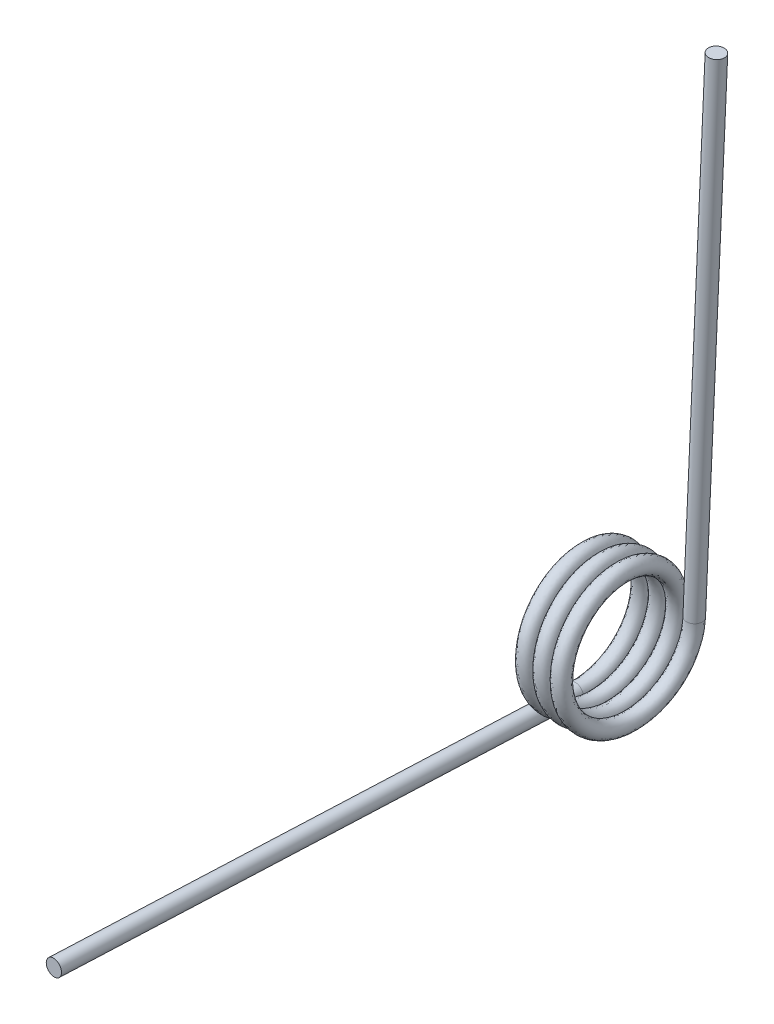
SolidWorks part; units mm, degrees
ref_plane "Front" through (0, 0, 0) normal (0, 0, 1) x (1, 0, 0)
ref_plane "Top" through (0, 0, 0) normal (0, 1, 0) x (1, 0, 0)
ref_plane "Right" through (0, 0, 0) normal (1, 0, 0) x (0, 0, -1)
sketch "Sketch1" plane through (0, 0, 0) normal (1, 0, 0) x (0, 0, -1)
  line L0 (0, 0) -> (0, -1.0287) construction
  line L1 (0, -1.0287) -> (0, -1.1811) construction
  line L2 (0, -1.1811) -> (0, -1.3335) construction
  circle A0 centre (0, 0) radius 1.0287 construction
  circle A1 centre (0, 0) radius 1.3335 construction
  circle A2 centre (0, 0) radius 1.1811
  circle A3 centre (0, -1.1811) radius 0.1524 construction
  circle A4 centre (0, 0) radius 0.8255 construction
  dimension "Wire Dia" = 0.3048
  dimension "Spring OD" = 2.667
  dimension "Max Rod OD" = 1.651
curve "Helix/Spiral1" pitch 0.3302 height 1.0731 turns 3.25
ref_plane "Plane1" through (0, -1.1811, 0) normal (0.0445, 0, -0.999) x (0.995, 0.0893, 0.0443)
sketch "Sketch2" plane through (0, -1.1811, 0) normal (0.0445, 0, -0.999) x (0.995, 0.0893, 0.0443)
  circle A0 centre (0, 0) radius 0.1524
  dimension "D1" = 0.3048
sweep "Sweep1" add profiles "Sketch2" path "Helix/Spiral1"
sketch "Sketch3" plane through (0, 0, 0) normal (-0.0445, 0, 0.999) x (-0.995, -0.0893, -0.0443)
  circle A1 centre (0.1054, 1.1764) radius 0.1524
  circle A2 centre (0.1054, 1.1764) radius 0.1524
  dimension "D1" = 0
extrude "Extrude1" add sketch "Sketch3" along normal blind 9.525
sketch "Sketch4" plane through (0.0021, 0.0477, 0) normal (0.0445, 0.999, 0) x (0.995, -0.0443, -0.0893)
  circle A1 centre (1.1732, 1.0807) radius 0.1524
  circle A2 centre (1.1732, 1.0807) radius 0.1524
  dimension "D1" = 0
extrude "Extrude2" add sketch "Sketch4" along normal blind 9.525
sketch "Sketch5" plane through (0, 0, 0) normal (1, 0, 0) x (0, 0, -1)
  circle A0 centre (0, 0) radius 0.8255 construction
  circle A1 centre (0, 0) radius 0.8255
equation "\"D4@Helix/Spiral1\"=\"Wire Dia@Sketch1\"+.001"
equation "\"D1@Sketch2\"=\"Wire Dia@Sketch1\""
equation "\"D1@Extrude2\"=\"Leg Length@Extrude1\""
